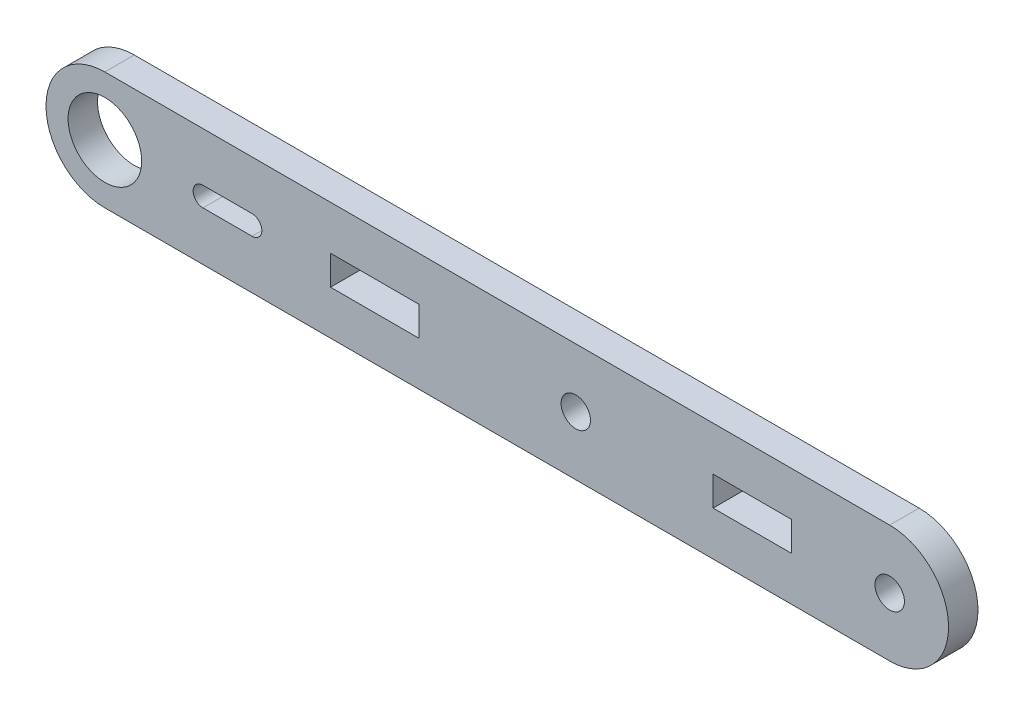
SolidWorks part; units mm, degrees
ref_plane "Plan de face" through (0, 0, 0) normal (0, 0, 1) x (1, 0, 0)
ref_plane "Plan de dessus" through (0, 0, 0) normal (0, 1, 0) x (1, 0, 0)
ref_plane "Plan de droite" through (0, 0, 0) normal (1, 0, 0) x (0, 0, -1)
sketch "Esquisse9" plane through (0, 0, 0) normal (0, 0, 1) x (1, 0, 0)
  line L0 (-63.0403, -53.5051) -> (16.9597, -53.5051) construction
  line L1 (-63.0403, -47.5051) -> (16.9597, -47.5051)
  line L2 (-63.0403, -59.5051) -> (16.9597, -59.5051)
  line L3 (-53.0403, -53.5051) -> (-48.0403, -53.5051) construction
  line L4 (-31.0403, -55.0051) -> (-40.0403, -55.0051)
  line L5 (-31.0403, -55.0051) -> (-31.0403, -52.0051)
  line L6 (-31.0403, -52.0051) -> (-40.0403, -52.0051)
  line L7 (-40.0403, -55.0051) -> (-40.0403, -52.0051)
  line L8 (6.9597, -55.0051) -> (-1.0403, -55.0051)
  line L9 (6.9597, -55.0051) -> (6.9597, -52.0051)
  line L10 (6.9597, -52.0051) -> (-1.0403, -52.0051)
  line L11 (-1.0403, -55.0051) -> (-1.0403, -52.0051)
  line L12 (-53.0403, -52.5051) -> (-48.0403, -52.5051)
  line L13 (-53.0403, -54.5051) -> (-48.0403, -54.5051)
  circle A0 centre (-15.0403, -53.5051) radius 1.5
  circle A1 centre (16.9597, -53.5051) radius 1.5
  circle A2 centre (-63.0403, -53.5051) radius 3.75
  arc A3 (-63.0403, -47.5051) -> (-63.0403, -59.5051) centre (-63.0403, -53.5051) ccw
  arc A4 (16.9597, -59.5051) -> (16.9597, -47.5051) centre (16.9597, -53.5051) ccw
  arc A5 (-53.0403, -52.5051) -> (-53.0403, -54.5051) centre (-53.0403, -53.5051) ccw
  arc A6 (-48.0403, -54.5051) -> (-48.0403, -52.5051) centre (-48.0403, -53.5051) ccw
  point P6 (-23.0403, -53.5051)
  point P21 (-50.5403, -53.5051)
  dimension "D1" = 3
  dimension "D2" = 3
  dimension "D3" = 7.5
  dimension "D4" = 6
  dimension "D11" = 32
  dimension "D15" = 1
  dimension "D5" = 8
  dimension "D6" = 9
  dimension "D7" = 3
  dimension "D8" = 3
  dimension "D9" = 1.5
  dimension "D10" = 1.5
  dimension "D12" = 80
  dimension "D13" = 30
  dimension "D14" = 10
  dimension "D16" = 5
  dimension "D17" = 17
extrude "Boss.-Extru.9" add sketch "Esquisse9" along normal blind 3 separate body
